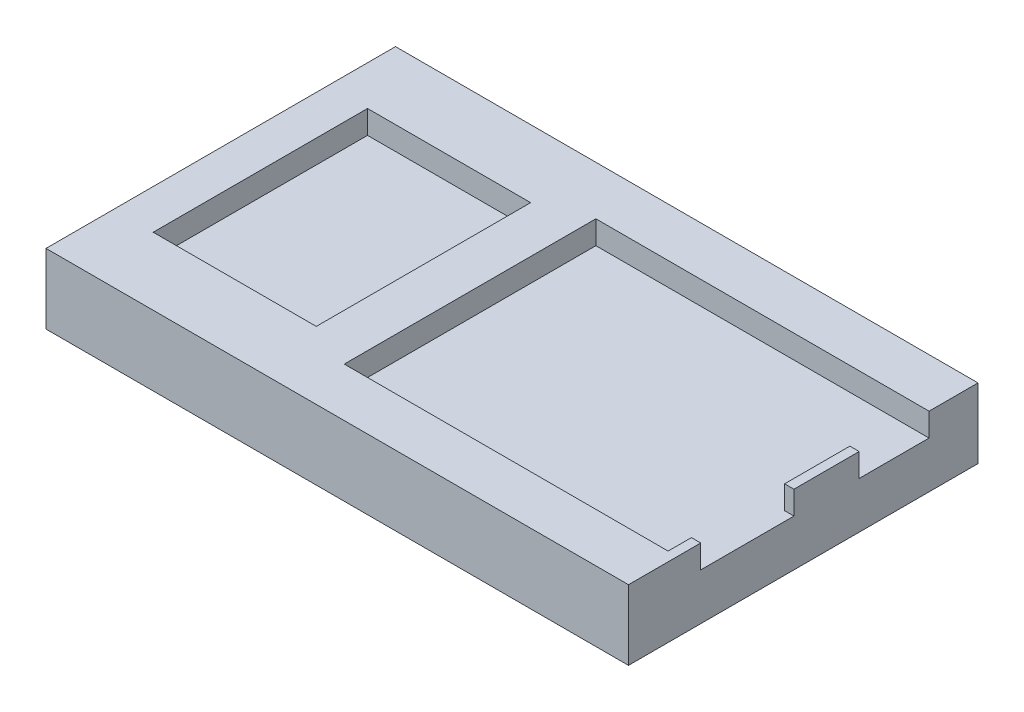
SolidWorks part; units mm, degrees
ref_plane "Front Plane" through (0, 0, 0) normal (0, 0, 1) x (1, 0, 0)
ref_plane "Top Plane" through (0, 0, 0) normal (0, 1, 0) x (1, 0, 0)
ref_plane "Right Plane" through (0, 0, 0) normal (1, 0, 0) x (0, 0, -1)
sketch "Sketch1" plane through (0, 0, 0) normal (0, 1, 0) x (1, 0, 0)
  line L1 (0, 0) -> (125, 0)
  line L2 (0, 0) -> (0, 75)
  line L3 (0, 75) -> (125, 75)
  line L4 (125, 0) -> (125, 75)
  dimension "D1" = 125
  dimension "D2" = 75
extrude "Boss-Extrude1" add sketch "Sketch1" along normal blind 15
sketch "Sketch2" plane through (0, 15, 0) normal (0, 1, 0) x (1, 0, 0)
  line L0 (125, 0) -> (125, 75) construction
  line L1 (53.5, 64.5) -> (125, 64.5)
  line L2 (53.5, 64.5) -> (53.5, 10.5)
  line L3 (53.5, 10.5) -> (123, 10.5)
  line L4 (123, 49.5) -> (123, 35.5)
  line L5 (123, 15.5) -> (123, 10.5)
  line L6 (125, 15.5) -> (123, 15.5)
  line L7 (125, 15.5) -> (125, 35.5)
  line L8 (125, 35.5) -> (123, 35.5)
  line L11 (125, 64.5) -> (125, 49.5)
  line L12 (125, 49.5) -> (123, 49.5)
  line L15 (8.5, 60.5) -> (43.5, 60.5)
  line L16 (8.5, 60.5) -> (8.5, 14.5)
  line L17 (8.5, 14.5) -> (43.5, 14.5)
  line L18 (43.5, 60.5) -> (43.5, 14.5)
  point P6 (125, 37.5)
  point P9 (53.5, 37.5)
  point P19 (43.5, 37.5)
  dimension "D1" = 2
  dimension "D2" = 54
  dimension "D3" = 69.5
  dimension "D4" = 5
  dimension "D5" = 20
  dimension "D6" = 15
  dimension "D7" = 35
  dimension "D8" = 46
  dimension "D9" = 10
extrude "Cut-Extrude4" cut sketch "Sketch2" against normal blind 5
sketch "Sketch3" plane through (0, 0, 0) normal (0, -1, 0) x (1, 0, 0)
  line L0 (0, -75) -> (0, 0) construction
  line L1 (20.6, -52.5) -> (15, -52.5)
  line L2 (20.6, -52.5) -> (20.6, -22.5)
  line L3 (20.6, -22.5) -> (15, -22.5)
  line L4 (15, -52.5) -> (15, -22.5)
  line L5 (62.5, -75) -> (62.5, 0) construction
  line L6 (125, -75) -> (0, -75) construction
  line L7 (0, 0) -> (125, 0) construction
  line L8 (104.4, -22.5) -> (110, -22.5)
  line L9 (110, -52.5) -> (110, -22.5)
  line L10 (104.4, -52.5) -> (110, -52.5)
  line L11 (104.4, -52.5) -> (104.4, -22.5)
  point P6 (15, -37.5)
  point P7 (0, -37.5)
  dimension "D1" = 15
  dimension "D2" = 5.6
  dimension "D3" = 30
extrude "Cut-Extrude5" cut sketch "Sketch3" against normal blind 5
